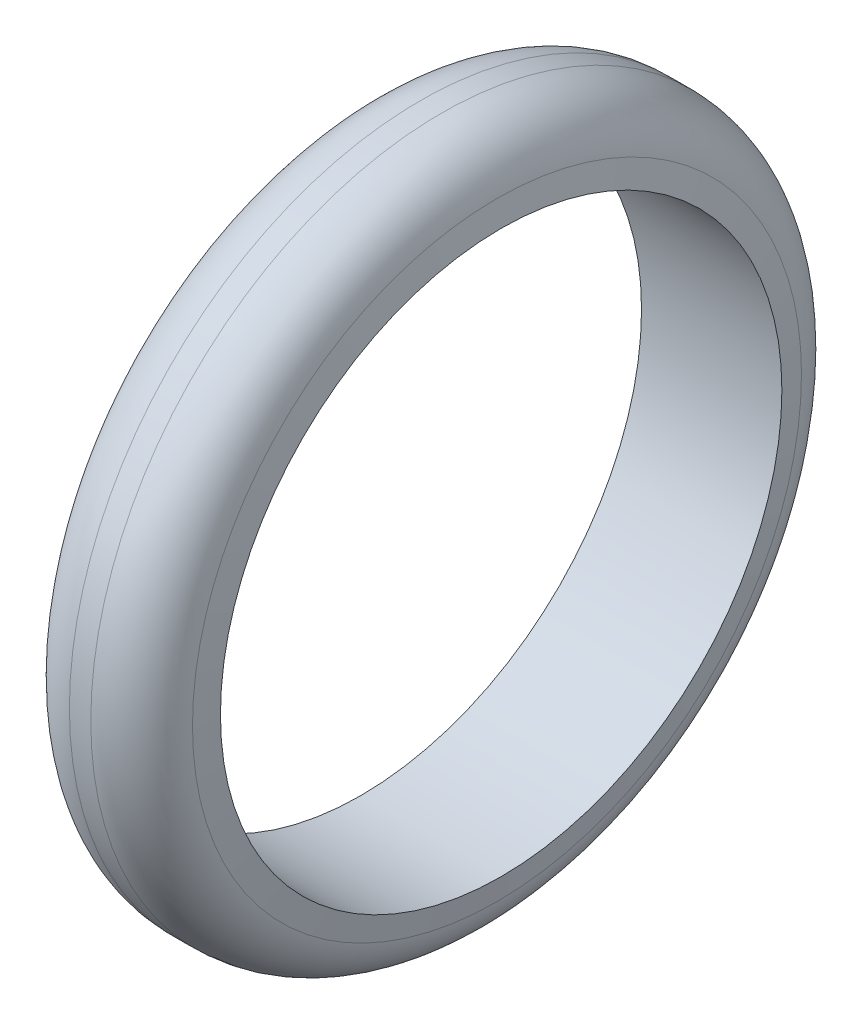
SolidWorks part; units mm, degrees
ref_plane "Front Plane" through (0, 0, 0) normal (0, 0, 1) x (1, 0, 0)
ref_plane "Top Plane" through (0, 0, 0) normal (0, 1, 0) x (1, 0, 0)
ref_plane "Right Plane" through (0, 0, 0) normal (1, 0, 0) x (0, 0, -1)
sketch "Sketch2" plane through (0, 0, 0) normal (0, 0, 1) x (1, 0, 0)
  line L0 (0, 0) -> (0, 64.6667) construction
  line L1 (0, 0) -> (72.5616, 0) construction
  line L2 (-8.2367, 50) -> (8.2367, 50)
  line L3 (-10, 40) -> (10, 40)
  line L4 (8.2367, 50) -> (10, 40)
  line L5 (-8.2367, 50) -> (-10, 40)
  dimension "D1" = 80
  dimension "D2" = 100
  dimension "D3" = 10
  dimension "D4" = 20
revolve "Revolve2" add sketch "Sketch2" angle 360 about L1
fillet "Fillet1" radius 8 2 edges at (8.2367, 0, 50) (-8.2367, 0, 50)
